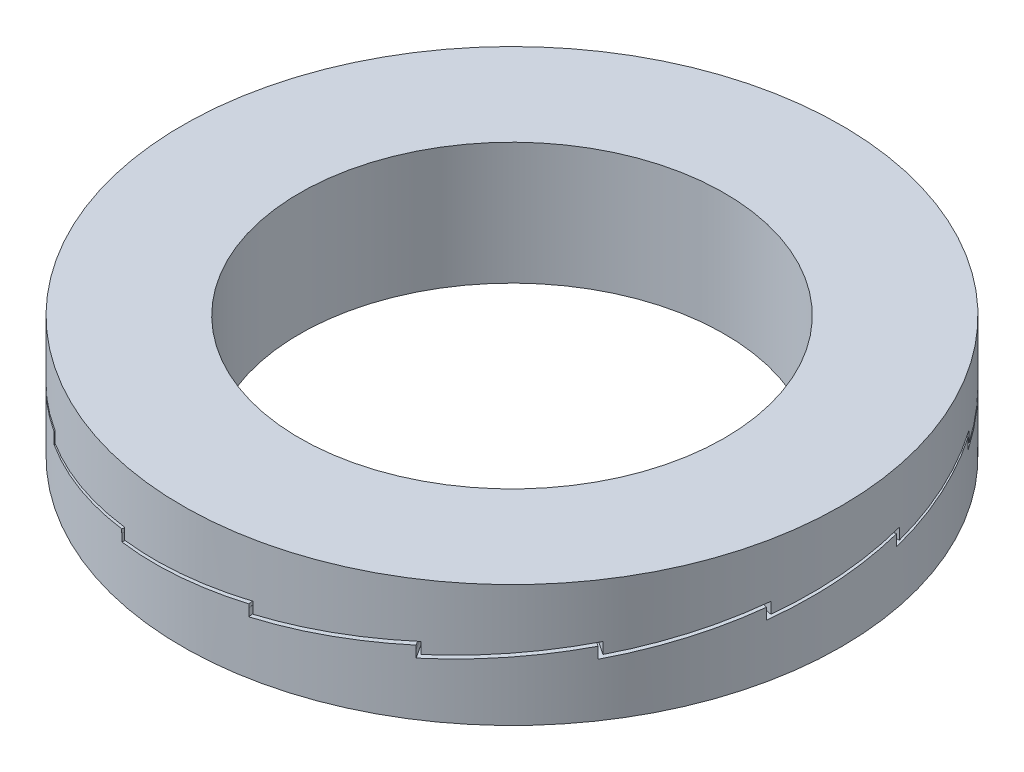
SolidWorks part; units mm, degrees
material "PW100:Mi:0:30:Re:13:"
ref_plane "Front" through (0, 0, 0) normal (0, 0, 1) x (1, 0, 0)
ref_plane "Top" through (0, 0, 0) normal (0, 1, 0) x (1, 0, 0)
ref_plane "Right" through (0, 0, 0) normal (1, 0, 0) x (0, 0, -1)
sketch "Support-Top-Body" plane through (0, 0, 0) normal (0, 1, 0) x (1, 0, 0)
  line L0 (0, 0) -> (4.35, 0) construction
  line L1 (4.35, 0) -> (6.75, 0) construction
  circle A0 centre (0, 0) radius 6.75
  circle A1 centre (0, 0) radius 4.35
  dimension "Diam-Inner" = 8.7
  dimension "Diam-Outer" = 13.5
sketch "Support-Front-Body" plane through (0, 0, 0) normal (0, 0, 1) x (1, 0, 0)
  line L0 (4.35, 1.15) -> (4.45, 1.25)
  line L1 (4.35, 1.25) -> (6.75, 1.25)
  line L2 (4.35, 1.25) -> (4.35, -1.25)
  line L3 (4.35, -1.25) -> (6.75, -1.25)
  line L4 (6.75, 1.25) -> (6.75, -1.25)
  line L5 (0, -1.25) -> (0, 1.25) construction
  line L6 (4.35, 1.25) -> (0, 1.25) construction
  line L7 (4.35, -1.25) -> (0, -1.25) construction
  line L8 (4.35, -1.15) -> (4.45, -1.25)
  line L9 (6.75, 0) -> (0, 0) construction
  dimension "Thickness" = 2.5
  dimension "Angel-Cut" = 45
  dimension "Dist-Cut" = 0.1
sketch "Sketch3" plane through (0, 0, 0) normal (0, 0, 1) x (1, 0, 0)
  line L0 (0, -1.25) -> (0, 1.25) construction
  line L1 (0, -1.25) -> (0, 1.25) construction
  line L4 (6.75, 1.25) -> (4.35, 1.25)
  line L5 (6.75, -1.25) -> (6.75, 1.25)
  line L6 (4.35, -1.25) -> (6.75, -1.25)
  line L7 (4.35, 1.25) -> (4.35, -1.25)
  line L8 (6.75, 1.25) -> (4.35, 1.25)
  line L9 (6.75, -1.25) -> (6.75, 1.25)
  line L10 (4.35, -1.25) -> (6.75, -1.25)
  line L11 (4.35, 1.25) -> (4.35, -1.25)
  dimension "D1" = 0
revolve "Base-Revolve" add sketch "Sketch3" angle 360 about L1
sketch "Support-Top-Cut" plane through (0, 0, 0) normal (0, 1, 0) x (1, 0, 0)
  line L0 (6.207, 0) -> (6.75, 0)
  line L1 (6.207, 0) -> (6.207, 6.207) construction
  line L3 (6.207, 6.207) -> (0, 6.207) construction
  line L5 (6.207, 6.207) -> (6.75, 0) construction
  line L6 (0, 0) -> (0, 6.207) construction
  line L7 (0, 0) -> (6.207, 0) construction
  line L8 (0, 0) -> (6.0877, 1.2109) construction
  line L9 (0, 0) -> (6.0877, -1.2109) construction
  line L10 (6.0877, 1.2109) -> (6.75, 1.3427)
  line L11 (6.0877, -1.2109) -> (6.75, -1.3427)
  line L12 (6.207, -1.2346) -> (6.207, 1.2346) construction
  line L13 (6.75, -1.3427) -> (6.75, 1.3427) construction
  circle A0 centre (0, 0) radius 6.207 construction
  dimension "Angle-Cut-Length" = 5
ref_plane "Plane-Cut-Start" through (6.207, 0, 0) normal (1, 0, 0) x (0, 0, -1)
ref_plane "Plane-Cut-End" through (6.75, 0, 0) normal (1, 0, 0) x (0, 0, -1)
sketch "Support-Plane-Cut-Start" plane through (6.207, 0, 0) normal (1, 0, 0) x (0, 0, -1)
  line L0 (-1.3026, 0) -> (-1.2346, 0)
  line L1 (-1.2346, 0) -> (-1.2346, -0.0739)
  line L2 (-1.2346, -0.0739) -> (1.2346, 0.1421)
  line L3 (1.2346, 0.1421) -> (1.2346, 0)
  line L4 (1.2346, 0) -> (1.1667, 0)
  line L5 (1.1667, 0) -> (1.1667, 0.068)
  line L6 (1.1667, 0.068) -> (-1.3026, -0.1481)
  line L7 (-1.3026, -0.1481) -> (-1.3026, 0)
  line L8 (4.35, 0) -> (-4.35, 0) construction
  line L13 (1.1667, 0.068) -> (1.1608, 0.1357) construction
  line L14 (0, -0.0341) -> (0, 0.0341) construction
  dimension "Angle-Cut" = 5
sketch "Sketch12" plane through (6.207, 0, 0) normal (1, 0, 0) x (0, 0, -1)
  line L8 (-1.3026, -0.1481) -> (1.1667, 0.068)
  line L9 (1.1667, 0.068) -> (1.1667, 0)
  line L10 (1.1667, 0) -> (1.2346, 0)
  line L11 (1.2346, 0) -> (1.2346, 0.1421)
  line L12 (1.2346, 0.1421) -> (-1.2346, -0.0739)
  line L13 (-1.2346, -0.0739) -> (-1.2346, 0)
  line L14 (-1.2346, 0) -> (-1.3026, 0)
  line L15 (-1.3026, 0) -> (-1.3026, -0.1481)
  line L16 (-1.3026, -0.1481) -> (1.1667, 0.068)
  line L17 (1.1667, 0.068) -> (1.1667, 0)
  line L18 (1.1667, 0) -> (1.2346, 0)
  line L19 (1.2346, 0) -> (1.2346, 0.1421)
  line L20 (1.2346, 0.1421) -> (-1.2346, -0.0739)
  line L21 (-1.2346, -0.0739) -> (-1.2346, 0)
  line L22 (-1.2346, 0) -> (-1.3026, 0)
  line L23 (-1.3026, 0) -> (-1.3026, -0.1481)
  dimension "D1" = 0
sketch "Sketch15" plane through (6.75, 0, 0) normal (1, 0, 0) x (0, 0, -1)
  line L0 (-1.4193, 0) -> (-1.3427, 0)
  line L1 (-1.3427, 0) -> (-1.3427, -0.0834)
  line L2 (-1.3427, -0.0834) -> (1.3427, 0.1516)
  line L3 (1.3427, 0.1516) -> (1.3427, 0)
  line L4 (1.3427, 0) -> (1.266, 0)
  line L5 (1.266, 0) -> (1.266, 0.0767)
  line L6 (1.266, 0.0767) -> (-1.4193, -0.1583)
  line L7 (-1.4193, -0.1583) -> (-1.4193, 0)
  line L8 (-1.3427, 0) -> (1.3427, 0) construction
  line L9 (-1.3026, -0.1481) -> (1.1667, 0.068) construction
  line L10 (6.207, 0) -> (-6.207, 0) construction
  line L11 (1.2346, 0.1421) -> (-1.2346, -0.0739) construction
loft "Cut-Profile" cut profiles "Sketch12", "Sketch15"
pattern_circular "Pattern-Cut-Profile" count 16 every 22.5 about axis through (0, -1.25, 0) along (0, 1, 0) of "Cut-Profile"
sketch "Sketch17" plane through (0, 0, 0) normal (0, 0, 1) x (1, 0, 0)
  line L0 (4.35, 1.25) -> (4.35, -1.25) construction
  line L1 (4.35, 1.25) -> (6.75, 1.25) construction
  line L2 (4.35, 1.15) -> (4.45, 1.25) construction
  line L4 (4.35, 1.25) -> (4.45, 1.25)
  line L5 (4.35, 1.15) -> (4.45, 1.25)
  line L6 (0, 0) -> (0, 1.25) construction
  line L7 (0, -1.25) -> (0, 1.25) construction
  line L8 (4.35, -1.15) -> (4.45, -1.25) construction
  line L9 (4.35, -1.25) -> (6.75, -1.25) construction
  line L10 (4.35, -1.15) -> (4.45, -1.25)
  line L11 (4.35, -1.25) -> (4.45, -1.25)
  line L12 (4.35, 1.25) -> (4.35, 1.15)
  line L13 (4.35, -1.15) -> (4.35, -1.25)
revolve "Cosmetic-Cut" [suppressed] cut sketch "Sketch17" angle 360 about L6
equation "\"Num-Cut-Profile@Pattern-Cut-Profile\" =360 / \"Angle-Cut-Width@Pattern-Cut-Profile\""
